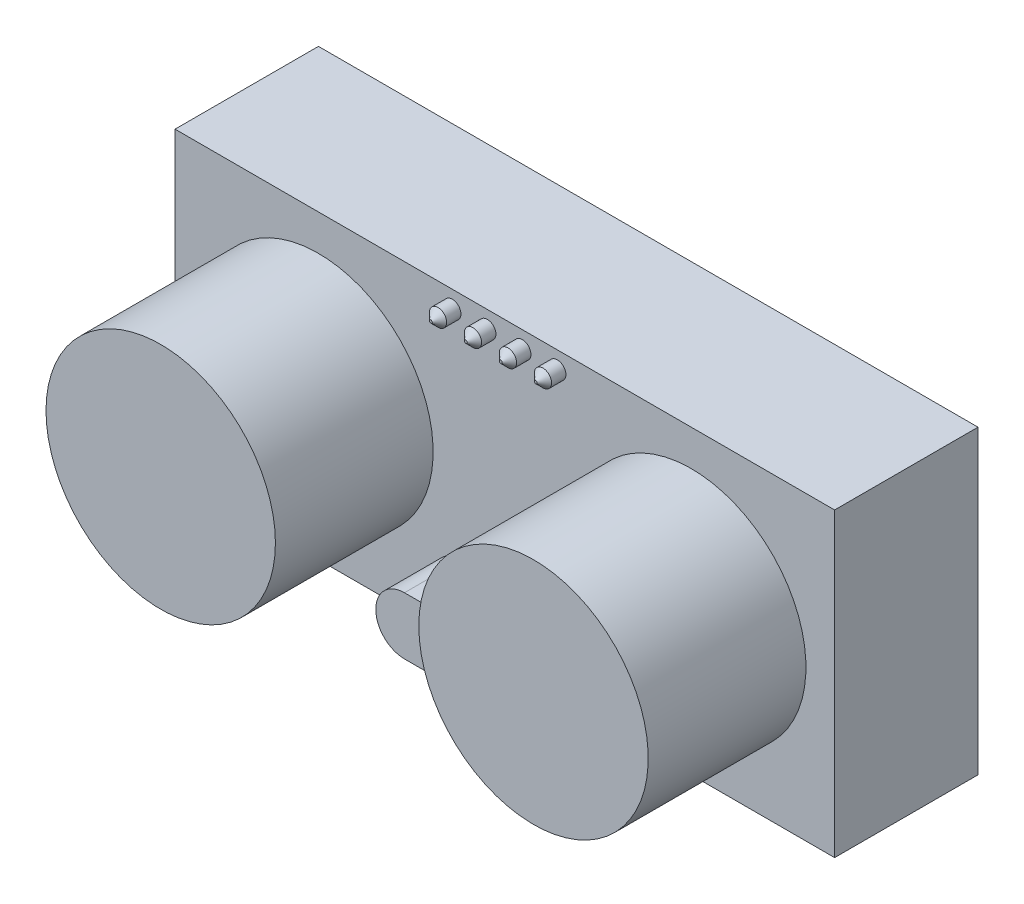
SolidWorks part; units mm, degrees
ref_plane "Płaszczyzna przednia" through (0, 0, 0) normal (0, 0, 1) x (1, 0, 0)
ref_plane "Płaszczyzna górna" through (0, 0, 0) normal (0, 1, 0) x (1, 0, 0)
ref_plane "Płaszczyzna prawa" through (0, 0, 0) normal (1, 0, 0) x (0, 0, -1)
sketch "Szkic1" plane through (0, 0, 0) normal (0, 0, 1) x (1, 0, 0)
  line L1 (-23, -10.5) -> (23, -10.5)
  line L2 (-23, -10.5) -> (-23, 10.5)
  line L3 (-23, 10.5) -> (23, 10.5)
  line L4 (23, -10.5) -> (23, 10.5)
  line L5 (-23, -10.5) -> (23, 10.5) construction
  line L6 (-23, 10.5) -> (23, -10.5) construction
  point P0 (0, 0)
  dimension "D1" = 21
  dimension "D2" = 46
extrude "Dodanie-wyciągnięcie1" add sketch "Szkic1" along normal blind 10
sketch "Szkic2" plane through (0, 0, 10) normal (0, 0, 1) x (1, 0, 0)
  line L0 (0, 0) -> (0, 10.5) construction
  line L1 (23, 10.5) -> (-23, 10.5) construction
  circle A0 centre (-13, 0) radius 8
  circle A1 centre (13, 0) radius 8
  dimension "D1" = 16
  dimension "D2" = 26
extrude "Dodanie-wyciągnięcie2" add sketch "Szkic2" along normal blind 11
sketch "Szkic3" plane through (0, 0, 10) normal (0, 0, 1) x (1, 0, 0)
  line L0 (-3, -7.5) -> (3, -7.5) construction
  line L1 (-3, -5.5) -> (3, -5.5)
  line L2 (-3, -9.5) -> (3, -9.5)
  line L3 (-23, -10.5) -> (23, -10.5) construction
  arc A0 (-3, -5.5) -> (-3, -9.5) centre (-3, -7.5) ccw
  arc A1 (3, -9.5) -> (3, -5.5) centre (3, -7.5) ccw
  point P2 (0, -7.5)
  dimension "D1" = 4
  dimension "D2" = 6
  dimension "D3" = 1
extrude "Dodanie-wyciągnięcie3" add sketch "Szkic3" along normal blind 4
sketch "Szkic4" plane through (0, 0, 10) normal (0, 0, 1) x (1, 0, 0)
  line L0 (-3.66, 9.3) -> (3.66, 9.3) construction
  line L1 (0, 9.3) -> (0, 0) construction
  line L2 (23, 10.5) -> (-23, 10.5) construction
  circle A0 centre (-3.66, 9.3) radius 0.6
  circle A1 centre (-1.22, 9.3) radius 0.6
  circle A2 centre (3.66, 9.3) radius 0.6
  circle A3 centre (1.22, 9.3) radius 0.6
  dimension "D1" = 1.2
  dimension "D2" = 2.44
  dimension "D3" = 2.44
  dimension "D4" = 1.2
extrude "Dodanie-wyciągnięcie4" add sketch "Szkic4" along normal blind 1.5
chamfer "Sfazowanie1" distance 0.5 angle 45 4 edges at (-3.06, 9.3, 11.5) (-0.62, 9.3, 11.5) (0.62, 9.3, 11.5) (3.06, 9.3, 11.5)
